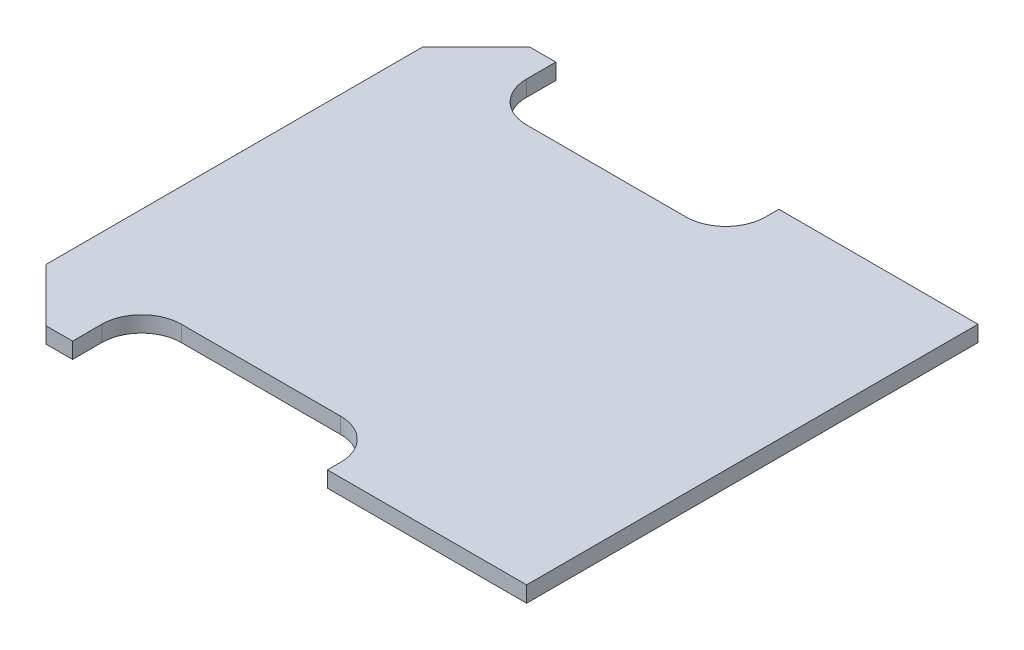
SolidWorks part; units mm, degrees
material "ABS"
ref_plane "Front Plane" through (0, 0, 0) normal (0, 0, 1) x (1, 0, 0)
ref_plane "Top Plane" through (0, 0, 0) normal (0, 1, 0) x (1, 0, 0)
ref_plane "Right Plane" through (0, 0, 0) normal (1, 0, 0) x (0, 0, -1)
sketch "Sketch1" plane through (0, 0, 0) normal (0, 1, 0) x (1, 0, 0)
  line L1 (-97.5, 85) -> (97.5, 85)
  line L2 (-97.5, 85) -> (-97.5, -85)
  line L3 (-97.5, -85) -> (97.5, -85)
  line L4 (97.5, 85) -> (97.5, -85)
  line L5 (-97.5, 85) -> (97.5, -85) construction
  line L6 (-97.5, -85) -> (97.5, 85) construction
  point P0 (0, 0)
  dimension "D1" = 195
  dimension "D2" = 170
extrude "Boss-Extrude1" add sketch "Sketch1" along normal blind 6
sketch "Sketch2" plane through (0, 6, 0) normal (0, 1, 0) x (1, 0, 0)
  line L0 (-97.5, -85) -> (-67.5, -85) construction
  line L1 (-97.5, -85) -> (97.5, -85) construction
  line L2 (0, 0) -> (-97.5, 0) construction
  line L3 (-67.5, -85) -> (22.5, -85)
  line L4 (-67.5, -85) -> (-67.5, -65)
  line L5 (-67.5, -65) -> (22.5, -65)
  line L6 (22.5, -85) -> (22.5, -65)
  line L7 (-97.5, 85) -> (-97.5, -85) construction
  line L8 (-67.5, 65) -> (22.5, 65)
  line L9 (22.5, 85) -> (22.5, 65)
  line L10 (-67.5, 85) -> (22.5, 85)
  line L11 (-67.5, 85) -> (-67.5, 65)
  dimension "D1" = 30
  dimension "D2" = 90
  dimension "D3" = 20
extrude "Cut-Extrude1" cut sketch "Sketch2" against normal through all
fillet "Fillet1" radius 15 4 edges at (22.5, 3, -65) (-67.5, 3, -65) (-67.5, 3, 65) (22.5, 3, 65)
sketch "Sketch3" plane through (0, 6, 0) normal (0, 1, 0) x (1, 0, 0)
  line L0 (0, 0) -> (-97.5, 0) construction
  line L1 (-67.5, 85) -> (-97.5, 85)
  line L2 (-67.5, 85) -> (-67.5, 91)
  line L3 (-67.5, 91) -> (-97.5, 91)
  line L4 (-97.5, 85) -> (-97.5, 91)
  line L5 (-97.5, 85) -> (-97.5, -85) construction
  line L6 (-67.5, -91) -> (-97.5, -91)
  line L7 (-97.5, -85) -> (-97.5, -91)
  line L8 (-67.5, -85) -> (-97.5, -85)
  line L9 (-67.5, -85) -> (-67.5, -91)
  dimension "D1" = 6
extrude "Boss-Extrude2" add sketch "Sketch3" against normal up to surface (6 mm away) up to face at (-16.875, 0, 0)
chamfer "Chamfer1" distance 20 angle 45 2 edges at (-97.5, 3, -91) (-97.5, 3, 91)
sketch "Sketch4" plane through (0, 0, 0) normal (0, -1, 0) x (1, 0, 0)
  line L0 (51.5, -75) -> (82.1667, -75) construction
  line L1 (143.5, -85) -> (51.5, -85) construction
  line L2 (143.5, -85) -> (143.5, -65) construction
  line L3 (143.5, -65) -> (51.5, -65) construction
  line L4 (51.5, -85) -> (51.5, -65) construction
  line L5 (82.1667, -75) -> (112.8333, -75) construction
  line L9 (97.5, -85) -> (22.5, -85) construction
  line L10 (112.8333, -75) -> (143.5, -75) construction
  line L11 (97.5, 85) -> (97.5, -85) construction
  line L12 (0, 0) -> (97.5, 0) construction
  circle A0 centre (82.1667, -75) radius 4
  circle A1 centre (82.1667, 75) radius 4
  point P7 (97.5, -75)
  dimension "D3" = 8
  dimension "D1" = 92
  dimension "D2" = 20
extrude "Cut-Extrude2" cut sketch "Sketch4" against normal blind 4.2
sketch "Sketch5" plane through (0, 0, 0) normal (0, -1, 0) x (1, 0, 0)
  line L0 (82.1667, -75) -> (82.1667, 0) construction
  line L1 (82.1667, 0) -> (0, 0) construction
  line L2 (76.0167, 66) -> (88.3167, 66)
  line L3 (76.0167, -53.7) -> (88.3167, -53.7)
  line L4 (76.0167, -53.7) -> (76.0167, -66)
  line L5 (76.0167, -66) -> (88.3167, -66)
  line L6 (88.3167, -53.7) -> (88.3167, -66)
  line L7 (76.0167, -53.7) -> (88.3167, -66) construction
  line L8 (76.0167, -66) -> (88.3167, -53.7) construction
  line L9 (88.3167, 53.7) -> (88.3167, 66)
  line L10 (76.0167, 53.7) -> (88.3167, 53.7)
  line L11 (76.0167, 53.7) -> (76.0167, 66)
  point P3 (82.1667, -59.85)
  dimension "D1" = 9
  dimension "D2" = 12.3
  dimension "D3" = 12.3
extrude "Cut-Extrude3" cut sketch "Sketch5" against normal blind 4.2
sketch "Sketch6" plane through (0, 4.2, 0) normal (0, -1, 0) x (1, 0, 0)
  line L0 (0, 0) -> (97.5, 0) construction
  line L1 (76.0167, -66) -> (88.3167, -66)
  line L2 (76.0167, -66) -> (76.0167, -81.15)
  line L3 (76.0167, -81.15) -> (88.3167, -81.15)
  line L4 (88.3167, -66) -> (88.3167, -81.15)
  line L5 (97.5, 85) -> (97.5, -85) construction
  line L6 (76.0167, 81.15) -> (88.3167, 81.15)
  line L7 (76.0167, 66) -> (76.0167, 81.15)
  line L8 (76.0167, 66) -> (88.3167, 66)
  line L9 (88.3167, 66) -> (88.3167, 81.15)
  circle A0 centre (82.1667, -75) radius 6.15 construction
  dimension "D1" = 12.3
extrude "Cut-Extrude4" cut sketch "Sketch6" along normal blind 3.2
